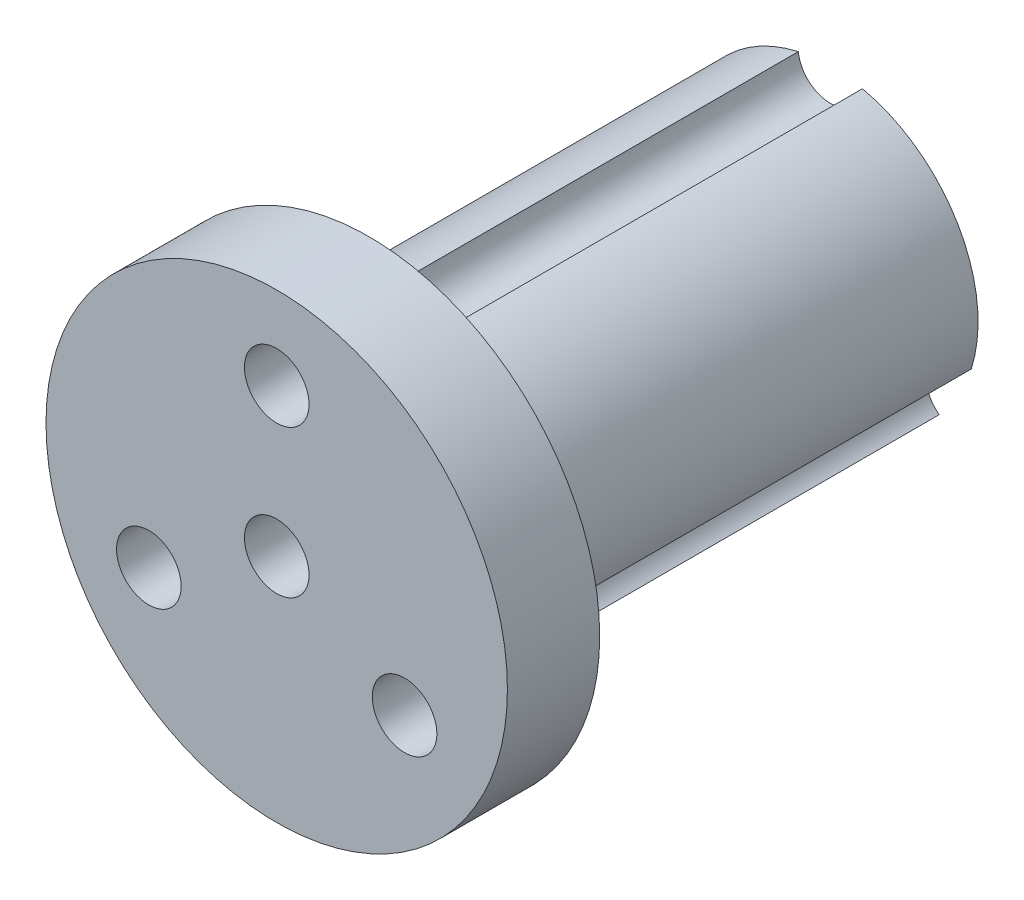
SolidWorks part; units mm, degrees
ref_plane "前视基准面" through (0, 0, 0) normal (0, 0, 1) x (1, 0, 0)
ref_plane "上视基准面" through (0, 0, 0) normal (0, 1, 0) x (1, 0, 0)
ref_plane "右视基准面" through (0, 0, 0) normal (1, 0, 0) x (0, 0, -1)
sketch "草图1" plane through (0, 0, 0) normal (0, 0, 1) x (1, 0, 0)
  circle A0 centre (0, 0) radius 8
  dimension "D1" = 16
extrude "凸台-拉伸1" add sketch "草图1" along normal blind 25
sketch "草图2" plane through (0, 0, 25) normal (0, 0, 1) x (1, 0, 0)
  circle A0 centre (0, 0) radius 12.5
  dimension "D1" = 25
extrude "凸台-拉伸2" add sketch "草图2" along normal blind 5
sketch "草图3" plane through (0, 0, 30) normal (0, 0, 1) x (1, 0, 0)
  line L0 (0, 8) -> (-6.9282, -4) construction
  line L1 (0, 8) -> (0, 0) construction
  line L2 (6.9282, -4) -> (0, 8) construction
  circle A0 centre (0, 0) radius 1.75
  circle A1 centre (0, 0) radius 8 construction
  circle A2 centre (0, 8) radius 1.75
  circle A3 centre (-6.9282, -4) radius 1.75
  circle A4 centre (6.9282, -4) radius 1.75
  dimension "D1" = 16
  dimension "D2" = 3.5
  dimension "D3" = 3.5
  dimension "D4" = 30
  dimension "D5" = 30
extrude "切除-拉伸1" cut sketch "草图3" against normal blind 38
